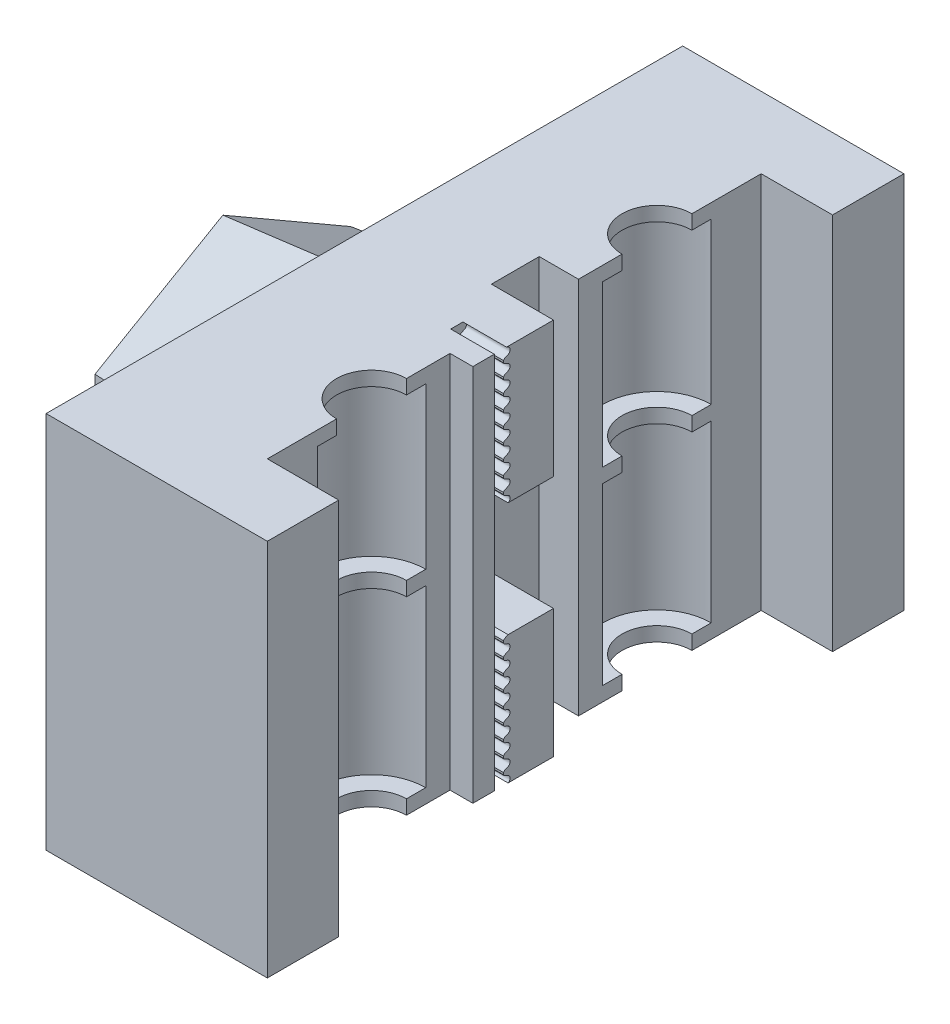
SolidWorks part; units mm, degrees
ref_plane "Front Plane" through (0, 0, 0) normal (0, 0, 1) x (1, 0, 0)
ref_plane "Top Plane" through (0, 0, 0) normal (0, 1, 0) x (1, 0, 0)
ref_plane "Right Plane" through (0, 0, 0) normal (1, 0, 0) x (0, 0, -1)
sketch "Sketch1" plane through (0, 0, 0) normal (0, 1, 0) x (1, 0, 0)
  line L0 (0, 36.6) -> (0, 43.6)
  line L1 (0, 43.6) -> (10, 43.6)
  line L2 (10, 43.6) -> (10, 53.6)
  line L3 (10, 53.6) -> (-21, 53.6)
  line L5 (-21, -35.6) -> (10, -35.6)
  line L6 (10, -35.6) -> (10, -25.6)
  line L7 (10, -25.6) -> (0, -25.6)
  line L8 (0, -25.6) -> (0, -18.6)
  line L9 (0, 21.4) -> (0, -3.4) construction
  line L10 (0, 18) -> (-5.5, 18)
  line L11 (-5.5, 18) -> (-5.5, 0)
  line L12 (-5.5, 0) -> (0, 0)
  line L24 (-21, 53.6) -> (-21, -35.6)
  line L25 (0, 0) -> (0, -3.4)
  line L26 (0, 18) -> (0, 21.4)
  arc A1 (0, 21.4) -> (0, 36.6) centre (0, 29) cw
  arc A2 (0, -18.6) -> (0, -3.4) centre (0, -11) cw
  dimension "D2" = 7.6
  dimension "D3" = 7.6
  dimension "D4" = 7
  dimension "D5" = 7
  dimension "D6" = 10
  dimension "D7" = 10
  dimension "D8" = 18
  dimension "D9" = 10
  dimension "D10" = 10
  dimension "D11" = 5.5
  dimension "D12" = 3.4
  dimension "D13" = 3.4
  dimension "D14" = 31
  dimension "D15" = 40
extrude "Boss-Extrude1" add sketch "Sketch1" along normal blind 53
sketch "Sketch2" plane through (0, 0, 0) normal (0, -1, 0) x (1, 0, 0)
  line L0 (0, 18.6) -> (0, 15.9)
  line L1 (0, 6.1) -> (0, 3.4)
  line L2 (0, -21.4) -> (0, -24.102)
  line L3 (0, -33.898) -> (0, -36.6)
  arc A0 (0, 3.4) -> (0, 18.6) centre (0, 11) cw
  arc A1 (0, 6.1) -> (0, 15.9) centre (0, 11) cw
  arc A2 (0, -36.6) -> (0, -21.4) centre (0, -29) cw
  arc A3 (0, -33.898) -> (0, -24.102) centre (0, -29) cw
  dimension "D1" = 4.9
  dimension "D2" = 4.898
extrude "Boss-Extrude2" add sketch "Sketch2" against normal blind 2
ref_plane "Plane1" through (0, 26.5, 0) normal (0, -1, 0) x (-1, 0, 0)
sketch "Sketch3" plane through (0, 26.5, 0) normal (0, -1, 0) x (-1, 0, 0)
  line L0 (0, -3.4) -> (0, -6.1)
  line L1 (0, -15.9) -> (0, -18.6)
  line L2 (0, 21.4) -> (0, 24.1)
  line L3 (0, 33.9) -> (0, 36.6)
  arc A0 (0, -18.6) -> (0, -3.4) centre (0, -11) ccw
  arc A1 (0, -15.9) -> (0, -6.1) centre (0, -11) ccw
  arc A2 (0, 36.6) -> (0, 21.4) centre (0, 29) cw
  arc A3 (0, 24.1) -> (0, 33.9) centre (0, 29) ccw
  dimension "D1" = 4.9
extrude "Boss-Extrude3" add sketch "Sketch3" against normal blind 2
ref_plane "Plane2" through (0, 51, 0) normal (0, -1, 0) x (-1, 0, 0)
sketch "Sketch4" plane through (0, 51, 0) normal (0, -1, 0) x (-1, 0, 0)
  line L0 (0, -18.6) -> (0, -15.9)
  line L1 (0, -6.1) -> (0, -3.4)
  line L2 (0, 36.6) -> (0, 33.9)
  line L3 (0, 24.1) -> (0, 21.4)
  arc A0 (0, -3.4) -> (0, -18.6) centre (0, -11) cw
  arc A1 (0, -15.9) -> (0, -6.1) centre (0, -11) ccw
  arc A2 (0, -15.9) -> (0, -6.1) centre (0, -11) ccw construction
  arc A3 (0, 21.4) -> (0, 36.6) centre (0, 29) ccw construction
  arc A5 (0, 24.1) -> (0, 33.9) centre (0, 29) ccw
  arc A6 (0, 21.4) -> (0, 36.6) centre (0, 29) ccw
  arc A7 (0, 24.1) -> (0, 33.9) centre (0, 29) ccw construction
extrude "Boss-Extrude4" add sketch "Sketch4" against normal blind 2
sketch "Sketch7" plane through (0, 53, 0) normal (0, 1, 0) x (1, 0, 0)
  line L0 (0, 0) -> (3.2, 0)
  line L1 (3.2, 0) -> (3.2, -2)
  line L2 (3.2, -2) -> (0, -2)
  line L3 (0, -6.1) -> (0, 0) construction
  line L4 (0, -2) -> (0, 0)
  dimension "D1" = 2
  dimension "D2" = 3.2
extrude "Boss-Extrude5" add sketch "Sketch7" against normal up to surface (53 mm away) up to face at (-1.4249, 0, -9)
sketch "Sketch8" plane through (0, 53, 0) normal (0, 1, 0) x (1, 0, 0)
  line L0 (0, 18) -> (0, 0) construction
  line L1 (-3.9424, 9) -> (6.0186, 9) construction
  line L2 (-5.5, 0) -> (3.2, 0)
  line L3 (3.2, 0) -> (-5.5, 0) construction
  line L4 (3.2, 0) -> (3.2, 3)
  line L5 (3.2, 3) -> (-5.5, 3)
  line L6 (-5.5, 0) -> (-5.5, 18) construction
  line L7 (-5.5, 3) -> (-5.5, 0)
  line L8 (3.2, -2) -> (3.2, 0) construction
  line L9 (-5.5, 11.3) -> (3.2, 11.3)
  line L10 (3.2, 11.3) -> (3.2, 4.3)
  line L11 (3.2, 4.3) -> (-5.5, 4.3)
  line L12 (-5.5, 4.3) -> (-5.5, 11.3)
  point P6 (0, 9)
  dimension "D1" = 3
  dimension "D2" = 7
  dimension "D3" = 1.3
extrude "Boss-Extrude6" add sketch "Sketch8" against normal up to surface (53 mm away) up to face at (-0.911, 0, -7.7778)
sketch "Sketch11" plane through (3.2, 0, 0) normal (1, 0, 0) x (0, 0, -1)
  line L0 (1264.5675, 560.6102) -> (1262.5675, 560.6102) construction
  line L1 (4.3, 0) -> (4.3, 53) construction
  line L2 (4.2853, 45.4328) -> (4.2853, 47.4569)
  spline S0 degree 3 poles (4.2853, 47.4569) (4.284, 47.4147) (4.2867, 47.3463) (4.3158, 47.2523) (4.3712, 47.1708) (4.4771, 47.1012) (4.6041, 47.0544) (4.7214, 46.9971) (4.8254, 46.9474) (4.9241, 46.9047) (5.0186, 46.8525) (5.1086, 46.7783) (5.1561, 46.6816) (5.1905, 46.5926) (5.1913, 46.5195) (5.1931, 46.4561) (5.1891, 46.3829) (5.1871, 46.2871) (5.1399, 46.1709) (5.0494, 46.057) (4.9087, 45.9856) (4.7554, 45.916) (4.621, 45.8529) (4.5075, 45.8004) (4.4122, 45.7562) (4.3028, 45.6419) (4.2855, 45.5136) (4.2853, 45.4328) knots 0 0 0 0 0.042789 0.068472 0.09859 0.140403 0.193951 0.235463 0.272242 0.310543 0.344117 0.381404 0.42616 0.451184 0.477135 0.499165 0.515432 0.551275 0.595353 0.639476 0.695379 0.752126 0.810504 0.845135 0.878871 0.916023 1 1 1 1
  line M5 (4.3, 53) -> (4.3, 0)
  dimension "D1" = 2
extrude "Cut-Extrude4" cut sketch "Sketch11" against normal up to surface (8.7 mm away) contours S0 M5 up to face at (-5.5, 26.5, -3.65)
pattern_linear "LPattern1" count 24 spacing 2 along (0, 1, 0) count 4 spacing 2 along (0, 1, 0) of "Cut-Extrude4"
sketch "Sketch12" plane through (3.2, 0, 0) normal (1, 0, 0) x (0, 0, -1)
  line L0 (11.3, 0) -> (11.3, 53) construction
  line L1 (11.3, 34) -> (4.3, 34)
  line L2 (11.3, 34) -> (11.3, 18)
  line L3 (11.3, 18) -> (4.3, 18)
  line L4 (4.3, 34) -> (4.3, 18)
  dimension "D1" = 18
  dimension "D2" = 19
extrude "Cut-Extrude5" cut sketch "Sketch12" against normal up to surface (8.7 mm away) up to face at (-5.5, 26.5, -14.65)
sketch "Sketch13" plane through (0, 53, 0) normal (0, 1, 0) x (1, 0, 0)
  line L0 (-5.5, 3) -> (-2.9059, 3)
  line L1 (3.2, 3) -> (-5.5, 3) construction
  line L6 (-2.9059, 3) -> (-2.9059, 7.169)
  line L7 (-2.9059, 7.169) -> (-5.5, 7.169)
  line L8 (-5.5, 18) -> (-5.5, 0) construction
  line L9 (-5.5, 7.169) -> (-5.5, 3)
extrude "Boss-Extrude16" add sketch "Sketch13" against normal up to surface (53 mm away) up to face at (-0.9545, 0, -8.1123)
sketch "Sketch14" plane through (0, 53, 0) normal (0, 1, 0) x (1, 0, 0)
  line L0 (0, 0) -> (0, -2)
  line L1 (0, -2) -> (3.2, -2)
  line L2 (3.2, -2) -> (3.2, 0)
  line L3 (3.2, -2) -> (3.2, 3) construction
  line L4 (3.2, 0) -> (0, 0)
extrude "Cut-Extrude6" cut sketch "Sketch14" against normal up to surface (53 mm away) up to face at (-0.7186, 0, -8.1123)
sketch "Sketch15" plane through (-21, 0, 0) normal (-1, 0, 0) x (0, 0, 1)
  line L1 (-7.169, 49) -> (-27.0876, 37.5)
  line L2 (-27.0876, 37.5) -> (-27.0876, 14.5)
  line L3 (-27.0876, 14.5) -> (-7.169, 3)
  line L4 (-7.169, 3) -> (12.7496, 14.5)
  line L5 (12.7496, 14.5) -> (12.7496, 37.5)
  line L6 (12.7496, 37.5) -> (-7.169, 49)
  line L7 (35.6, 53) -> (35.6, 0) construction
  line L8 (-7.169, 18) -> (-7.169, 34) construction
  circle A0 centre (-7.169, 26) radius 19.9186 construction
  point P10 (-9.4045, 40.389)
  point P13 (-7.169, 26)
  point P14 (-7.169, 26)
  point P15 (-7.169, 2.4976)
  dimension "D1" = 46
sketch "Sketch16" plane through (-2.9059, 0, 0) normal (1, 0, 0) x (0, 0, -1)
  line L0 (7.169, 34) -> (3, 34)
  line L1 (3, 0) -> (3, 53) construction
  line L2 (7.169, 18) -> (3, 18)
  line L3 (3, 18) -> (3, 34)
  line L4 (7.169, 34) -> (7.169, 18)
extrude "Cut-Extrude7" cut sketch "Sketch16" against normal up to surface (2.5941 mm away) up to face at (-5.5, 26.25, -11.9423)
ref_plane "Plane3" through (-39, 0, 0) normal (-1, 0, 0) x (0, 0, 1)
sketch "Sketch18" plane through (-39, 0, 0) normal (-1, 0, 0) x (0, 0, 1)
  line L1 (-7.169, 46.6906) -> (-25.0876, 36.3453)
  line L2 (-25.0876, 36.3453) -> (-25.0876, 15.6547)
  line L3 (-25.0876, 15.6547) -> (-7.169, 5.3094)
  line L4 (-7.169, 5.3094) -> (10.7496, 15.6547)
  line L5 (10.7496, 15.6547) -> (10.7496, 36.3453)
  line L6 (10.7496, 36.3453) -> (-7.169, 46.6906)
  line L7 (-27.0876, 37.5) -> (-27.0876, 14.5) construction
  circle A0 centre (-7.169, 26) radius 17.9186 construction
  dimension "D1" = 2
loft "Loft1" add profiles "Sketch15", "Sketch18"
